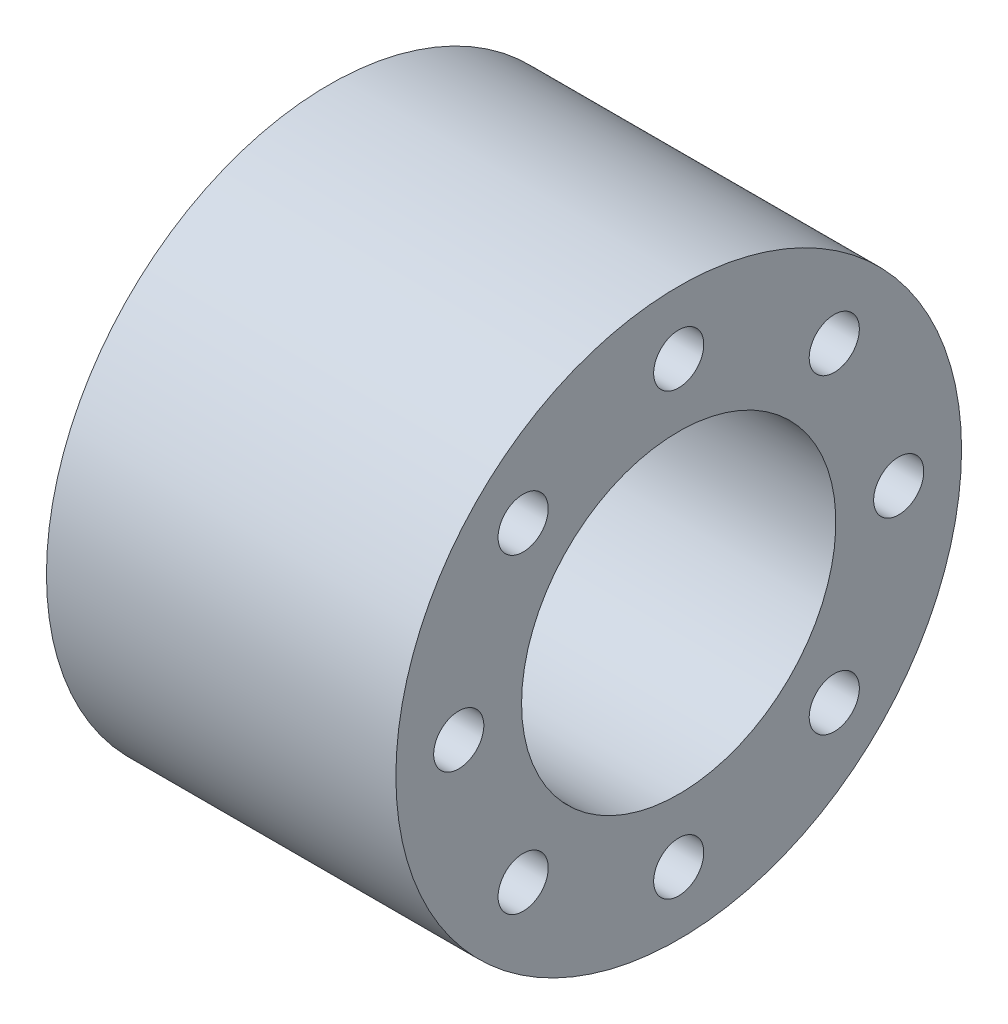
SolidWorks part; units mm, degrees
ref_plane "Front Plane" through (0, 0, 0) normal (0, 0, 1) x (1, 0, 0)
ref_plane "Top Plane" through (0, 0, 0) normal (0, 1, 0) x (1, 0, 0)
ref_plane "Right Plane" through (0, 0, 0) normal (1, 0, 0) x (0, 0, -1)
sketch "Sketch1" plane through (0, 0, 0) normal (0, 0, 1) x (1, 0, 0)
  line L0 (0, 0) -> (32.2114, 0) construction
  line L1 (0, 38.1) -> (47.0687, 38.1)
  line L2 (0, 38.1) -> (0, 21.1667)
  line L3 (0, 21.1667) -> (47.0687, 21.1667)
  line L4 (47.0687, 38.1) -> (47.0687, 21.1667)
  point P5 (0, 0)
  point P7 (0, 0)
  point P8 (0, 0)
  dimension "D1" = 76.2
  dimension "D2" = 42.3333
  dimension "D3" = 47.0687
revolve "Revolve1" add sketch "Sketch1" angle 360 about L0
sketch "Sketch4" plane through (0, 0, 0) normal (-1, 0, 0) x (0, 0, 1)
  circle A0 centre (0, 0) radius 29.6333 construction
  point P0 (0, 29.6333)
  point P11 (20.9539, 20.9539)
  point P12 (29.6333, 0)
  point P13 (20.9539, -20.9539)
  point P14 (0, -29.6333)
  point P15 (-20.9539, -20.9539)
  point P16 (-29.6333, 0)
  point P17 (-20.9539, 20.9539)
  dimension "D1" = 59.2667
  dimension "D2" = 8
hole_wizard "CBORE for 1/4 Socket Head Cap Screw1" positions "Sketch4" profile "Sketch3" counterbore size "1/4" standard "ANSI Inch" end condition up to next
sketch "Sketch3" plane through (0, 29.6333, 0) normal (0, 1, 0) x (0, 0, 1)
  line L0 (0, 0) -> (0, 47.0687)
  line L1 (0, 47.0687) -> (3.3782, 47.0687)
  line L3 (3.3782, 47.0687) -> (3.3782, 6.35)
  line L4 (3.3782, 6.35) -> (5.5562, 6.35)
  line L5 (5.5562, 6.35) -> (5.5563, 0)
  line L7 (5.5563, 0) -> (0, 0)
  line L11 (0, -6.35) -> (0, 107.95) construction
  dimension "Thru Hole Dia." = 6.7564
  dimension "Thru Hole Depth" = 47.0687
  dimension "C'Bore Dia." = 11.1125
  dimension "C'Bore Depth" = 6.35
sketch "Sketch7" plane through (0, 0, 0) normal (-1, 0, 0) x (0, 0, 1)
  line L0 (0, 0) -> (-11.5427, 27.8665) construction
  line L2 (0, 0) -> (0, 12.9917) construction
  circle A0 centre (0, 0) radius 30.1625 construction
  point P0 (-11.5427, 27.8665)
  point P21 (27.8665, 11.5427)
  point P22 (11.5427, -27.8665)
  point P23 (-27.8665, -11.5427)
  dimension "D1" = 60.325
  dimension "D2" = 22.5
  dimension "D3" = 4
hole_wizard "3/16 (0.1875) Dowel Hole1" positions "Sketch7" profile "Sketch6" hole size "3/16" standard "ANSI Inch"
sketch "Sketch6" plane through (0, 27.8665, -11.5427) normal (0, 1, 0) x (0, 0, 1)
  line L0 (0, 0) -> (0, 11.0828)
  line L1 (0, 11.0828) -> (2.3812, 9.652)
  line L2 (2.3812, 9.652) -> (2.3812, 0)
  line L5 (2.3812, 0) -> (0, 0)
  line L10 (0, 11.0828) -> (-2.3813, 9.652) construction
  line L11 (0, -6.35) -> (0, 107.95) construction
  dimension "Hole Dia." = 4.7625
  dimension "Hole Depth" = 9.652
  dimension "Drill Angle" = 118
equation "\"D1@Sketch4\"=(3+(1.75-1/12))/2"
